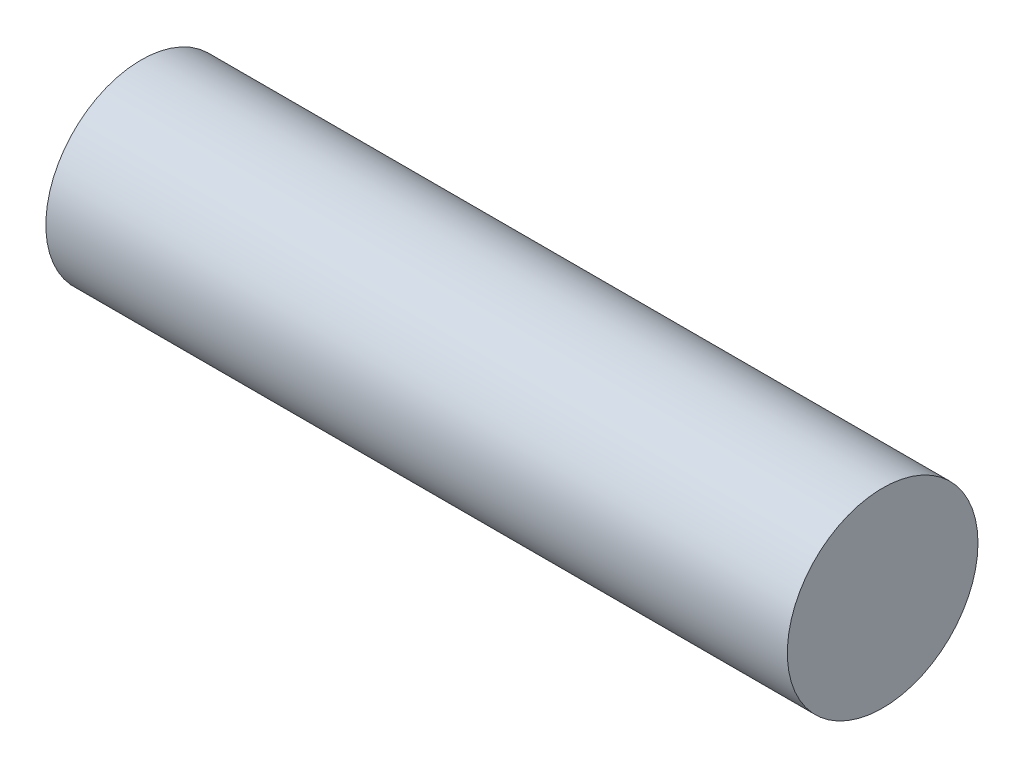
SolidWorks part; units mm, degrees
ref_plane "Front Plane" through (0, 0, 0) normal (1, 0, 0) x (0, 1, 0)
ref_plane "Top Plane" through (0, 0, 0) normal (0, 0, 1) x (0, 1, 0)
ref_plane "Right Plane" through (0, 0, 0) normal (0, 1, 0) x (-1, 0, 0)
sketch "Sketch1" plane through (0, 0, 0) normal (1, 0, 0) x (0, 1, 0)
  circle A0 centre (0, 0) radius 9
  dimension "D1" = 18
extrude "Boss-Extrude1" add sketch "Sketch1" along normal blind 70
